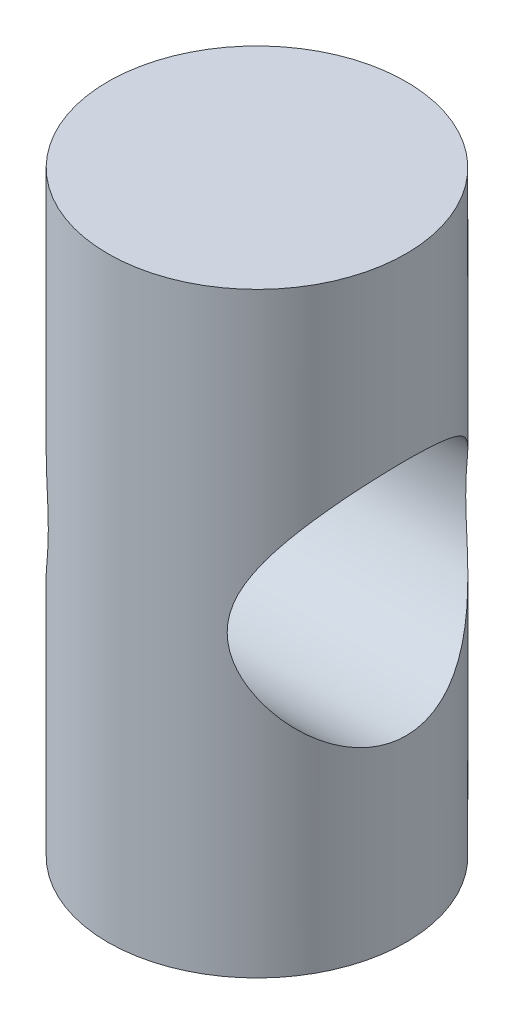
SolidWorks part; units mm, degrees
ref_plane "前视基准面" through (0, 0, 0) normal (0, 0, 1) x (1, 0, 0)
ref_plane "上视基准面" through (0, 0, 0) normal (0, 1, 0) x (1, 0, 0)
ref_plane "右视基准面" through (0, 0, 0) normal (1, 0, 0) x (0, 0, -1)
sketch "草图1" plane through (0, 0, 0) normal (0, 1, 0) x (1, 0, 0)
  circle A0 centre (0, 0) radius 5
extrude "凸台-拉伸1" add sketch "草图1" along normal blind 20
sketch "草图2" plane through (0, 0, 0) normal (1, 0, 0) x (0, 0, -1)
  line L0 (0, 5.5) -> (0, -5.5) construction
  circle A0 centre (0, 10) radius 4
extrude "切除-拉伸1" cut sketch "草图2" along normal through all both and the other way through all
